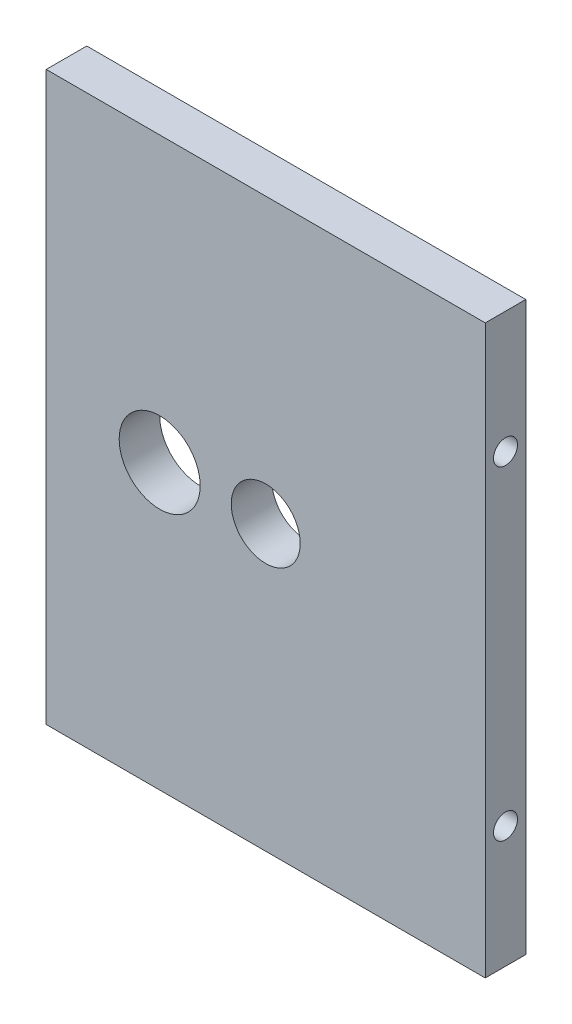
SolidWorks part; units mm, degrees
ref_plane "Front Plane" through (0, 0, 0) normal (0, 0, 1) x (1, 0, 0)
ref_plane "Top Plane" through (0, 0, 0) normal (0, 1, 0) x (1, 0, 0)
ref_plane "Right Plane" through (0, 0, 0) normal (1, 0, 0) x (0, 0, -1)
sketch "Sketch1" plane through (0, 0, 0) normal (0, 0, 1) x (1, 0, 0)
  line L1 (0, 0) -> (32.5, 0)
  line L2 (0, 0) -> (0, 42)
  line L3 (0, 42) -> (32.5, 42)
  line L4 (32.5, 0) -> (32.5, 42)
extrude "Boss-Extrude2" add sketch "Sketch1" along normal blind 3
sketch "Sketch2" plane through (0, 0, 3) normal (0, 0, 1) x (1, 0, 0)
  line L0 (0, 42) -> (0, 33)
  line L1 (0, 42) -> (0, 0) construction
  line L2 (0, 33) -> (32.5, 33)
  line L3 (32.5, 0) -> (32.5, 42) construction
  line L4 (0, 0) -> (0, 9)
  line L5 (0, 9) -> (32.5, 9)
sketch "Sketch3" plane through (0, 0, 0) normal (-1, 0, 0) x (0, 0, 1)
  line L0 (3, 33) -> (0, 33)
  line L1 (3, 42) -> (3, 33) construction
  line L2 (0, 42) -> (0, 0) construction
  line L3 (3, 9) -> (0, 9)
  line L4 (3, 0) -> (3, 9) construction
  line L5 (3, 42) -> (3, 0) construction
hole_wizard "#2-56 Tapped Hole1" positions "Sketch4" profile "Sketch5" tap size "#2-56" standard "ANSI Inch"
sketch "Sketch4" plane through (0, 0, 0) normal (-1, 0, 0) x (0, 0, 1)
  line L0 (3, 33) -> (0, 33) construction
  line L1 (3, 9) -> (0, 9) construction
  point P0 (1.5, 33)
  point P4 (1.5, 9)
sketch "Sketch5" plane through (0, 33, 1.5) normal (0, 1, 0) x (0, 0, 1)
  line L0 (0, 0) -> (0, 5.73)
  line L1 (0, 5.73) -> (0.889, 5.1958)
  line L2 (0.889, 5.1958) -> (0.889, 0)
  line L5 (0.889, 0) -> (0, 0)
  line L10 (0, 5.73) -> (-0.889, 5.1958) construction
  line L11 (0, -6.35) -> (0, 107.95) construction
  dimension "Tap Drill Dia." = 1.778
  dimension "Tap Drill Depth" = 5.73
  dimension "Drill Angle" = 118
cosmetic thread "Hole Thread1" parameters "D1"=4.37, "D2"=2.1844
cosmetic thread "Hole Thread2" parameters "D1"=4.37, "D2"=2.1844
sketch "Sketch6" plane through (32.5, 0, 0) normal (1, 0, 0) x (0, 0, -1)
  line L0 (-3, 33) -> (0, 33)
  line L1 (-3, 9) -> (0, 9)
hole_wizard "#2-56 Tapped Hole2" positions "Sketch7" profile "Sketch8" tap size "#2-56" standard "ANSI Inch"
sketch "Sketch7" plane through (32.5, 0, 0) normal (1, 0, 0) x (0, 0, -1)
  point P0 (-1.5, 33)
  point P3 (-1.5, 9)
sketch "Sketch8" plane through (32.5, 33, 1.5) normal (0, 1, 0) x (0, 0, -1)
  line L0 (0, 0) -> (0, 5.73)
  line L1 (0, 5.73) -> (0.889, 5.1958)
  line L2 (0.889, 5.1958) -> (0.889, 0)
  line L5 (0.889, 0) -> (0, 0)
  line L10 (0, 5.73) -> (-0.889, 5.1958) construction
  line L11 (0, -6.35) -> (0, 107.95) construction
  dimension "Tap Drill Dia." = 1.778
  dimension "Tap Drill Depth" = 5.73
  dimension "Drill Angle" = 118
cosmetic thread "Hole Thread3" parameters "D1"=4.37, "D2"=2.1844
cosmetic thread "Hole Thread4" parameters "D1"=4.37, "D2"=2.1844
sketch "Sketch9" plane through (0, 0, 0) normal (0, 0, -1) x (-1, 0, 0)
  line L0 (0, 21) -> (-32.5, 21)
  line L1 (0, 42) -> (0, 0) construction
  line L2 (-32.5, 0) -> (-32.5, 42) construction
  line L3 (-16.25, 21) -> (-8.4, 21)
  circle A0 centre (-8.4, 21) radius 3
extrude "Cut-Extrude1" cut sketch "Sketch9" against normal blind 3 contours L0 A0 | L0 A0
sketch "Sketch10" plane through (0, 0, 0) normal (0, 0, -1) x (-1, 0, 0)
  line L0 (-32.5, 42) -> (0, 0)
hole_wizard "1/4-20 Tapped Hole1" positions "Sketch11" profile "Sketch12" tap size "1/4-20" standard "ANSI Inch" end condition through all
sketch "Sketch11" plane through (0, 0, 0) normal (0, 0, -1) x (-1, 0, 0)
  line L0 (-32.5, 42) -> (0, 0) construction
  point P0 (-16.25, 21)
sketch "Sketch12" plane through (16.25, 21, 0) normal (1, 0, 0) x (0, 1, 0)
  line L0 (0, 0) -> (0, 3)
  line L1 (0, 3) -> (2.5527, 3)
  line L2 (2.5527, 3) -> (2.5527, 0)
  line L5 (2.5527, 0) -> (0, 0)
  line L11 (0, -6.35) -> (0, 107.95) construction
  dimension "Thru Tap Drill Dia." = 5.1054
  dimension "Thru Tap Drill Depth" = 3
cosmetic thread "Hole Thread5" parameters "D2"=6.35
